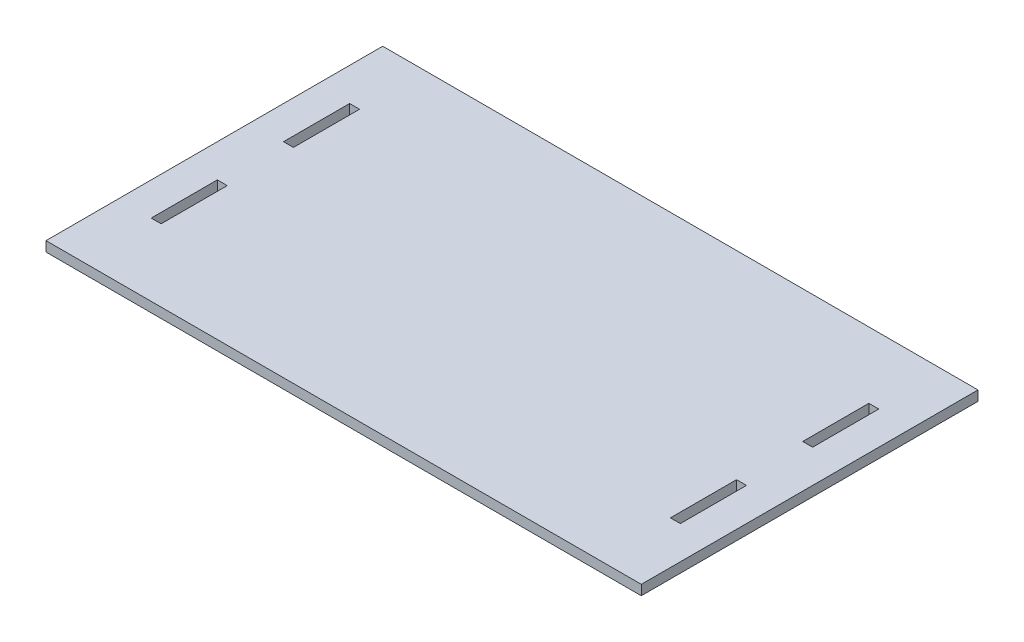
SolidWorks part; units mm, degrees
ref_plane "Front Plane" through (0, 0, 0) normal (0, 0, 1) x (1, 0, 0)
ref_plane "Top Plane" through (0, 0, 0) normal (0, 1, 0) x (1, 0, 0)
ref_plane "Right Plane" through (0, 0, 0) normal (1, 0, 0) x (0, 0, -1)
sketch "Sketch1" plane through (0, 0, 0) normal (0, 1, 0) x (1, 0, 0)
  line L1 (0, 0) -> (180, 0)
  line L2 (0, 0) -> (0, 101.81)
  line L3 (0, 101.81) -> (180, 101.81)
  line L4 (180, 0) -> (180, 101.81)
  dimension "D1" = 101.81
  dimension "D2" = 180
extrude "Boss-Extrude1" add sketch "Sketch1" along normal blind 3
sketch "Sketch2" plane through (0, 3, 0) normal (0, 1, 0) x (1, 0, 0)
  line L1 (10, 81.8066) -> (13, 81.8066)
  line L2 (10, 81.8066) -> (10, 61.8066)
  line L3 (10, 61.8066) -> (13, 61.8066)
  line L4 (13, 81.8066) -> (13, 61.8066)
  line L5 (10, 41.8066) -> (13, 41.8066)
  line L6 (10, 41.8066) -> (10, 21.8066)
  line L7 (10, 21.8066) -> (13, 21.8066)
  line L8 (13, 41.8066) -> (13, 21.8066)
  line L9 (167, 81.8066) -> (170, 81.8066)
  line L10 (167, 81.8066) -> (167, 61.8066)
  line L11 (167, 61.8066) -> (170, 61.8066)
  line L12 (170, 81.8066) -> (170, 61.8066)
  line L13 (167, 41.8066) -> (170, 41.8066)
  line L14 (167, 41.8066) -> (167, 21.8066)
  line L15 (167, 21.8066) -> (170, 21.8066)
  line L16 (170, 41.8066) -> (170, 21.8066)
extrude "Cut-Extrude1" cut sketch "Sketch2" against normal blind 3
